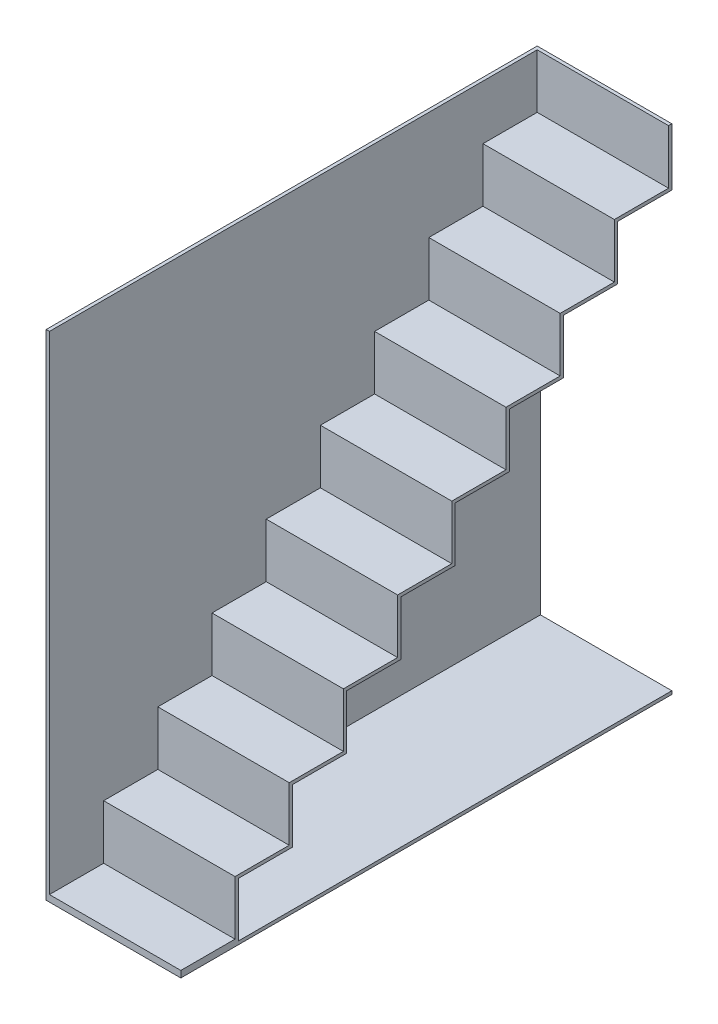
SolidWorks part; units mm, degrees
ref_plane "Front Plane" through (0, 0, 0) normal (0, 0, 1) x (1, 0, 0)
ref_plane "Top Plane" through (0, 0, 0) normal (0, 1, 0) x (1, 0, 0)
ref_plane "Right Plane" through (0, 0, 0) normal (1, 0, 0) x (0, 0, -1)
sketch "Sketch1" plane through (0, 0, 0) normal (1, 0, 0) x (0, 0, -1)
  line L0 (-23.9317, -26.5974) -> (-23.9317, 6.4026)
  line L1 (-25.9317, -24.5974) -> (-25.9317, 8.4026)
  line L3 (-25.9317, 8.4026) -> (7.0683, 8.4026)
  line L4 (-23.9317, 6.4026) -> (9.0683, 6.4026)
  line L6 (9.0683, 6.4026) -> (9.0683, 39.4026)
  line L7 (-23.9317, -26.5974) -> (-23.9317, 8.4026) construction
  line L8 (-25.9317, 6.4026) -> (9.0683, 6.4026) construction
  line L9 (7.0683, 8.4026) -> (7.0683, 41.4026)
  line L12 (-25.9317, 8.4026) -> (9.0683, 8.4026) construction
  line L13 (7.0683, 6.4026) -> (7.0683, 41.4026) construction
  line L14 (9.0683, 39.4026) -> (42.0683, 39.4026)
  line L16 (7.0683, 41.4026) -> (40.0683, 41.4026)
  line L17 (9.0683, 6.4026) -> (9.0683, 41.4026) construction
  line L18 (-23.9317, -26.5974) -> (-58.9317, -26.5974)
  line L19 (-25.9317, -24.5974) -> (-58.9317, -24.5974)
  line L20 (-58.9317, -24.5974) -> (-58.9317, -26.5974)
  line L22 (-25.9317, -26.5974) -> (-25.9317, 8.4026) construction
  line L23 (-23.9317, -24.5974) -> (-58.9317, -24.5974) construction
  line L24 (40.0683, 41.4026) -> (40.0683, 74.4026)
  line L26 (42.0683, 39.4026) -> (42.0683, 72.4026)
  line L27 (40.0683, 74.4026) -> (73.0683, 74.4026)
  line L28 (42.0683, 72.4026) -> (75.0683, 72.4026)
  line L30 (40.0683, 72.4026) -> (75.0683, 72.4026) construction
  line L31 (75.0683, 72.4026) -> (75.0683, 105.4026)
  line L32 (73.0683, 74.4026) -> (73.0683, 107.4026)
  line L34 (73.0683, 107.4026) -> (106.0683, 107.4026)
  line L35 (40.0683, 74.4026) -> (75.0683, 74.4026) construction
  line L36 (73.0683, 72.4026) -> (73.0683, 107.4026) construction
  line L37 (75.0683, 105.4026) -> (108.0683, 105.4026)
  line L39 (108.0683, 105.4026) -> (108.0683, 138.4026)
  line L40 (73.0683, 105.4026) -> (108.0683, 105.4026) construction
  line L41 (75.0683, 72.4026) -> (75.0683, 107.4026) construction
  line L42 (106.0683, 107.4026) -> (106.0683, 140.4026)
  line L44 (106.0683, 140.4026) -> (139.0683, 140.4026)
  line L45 (73.0683, 107.4026) -> (108.0683, 107.4026) construction
  line L46 (106.0683, 105.4026) -> (106.0683, 140.4026) construction
  line L47 (108.0683, 138.4026) -> (141.0683, 138.4026)
  line L49 (141.0683, 138.4026) -> (141.0683, 171.4026)
  line L50 (108.0683, 105.4026) -> (108.0683, 140.4026) construction
  line L51 (106.0683, 138.4026) -> (141.0683, 138.4026) construction
  line L52 (139.0683, 140.4026) -> (139.0683, 173.4026)
  line L54 (139.0683, 173.4026) -> (172.0683, 173.4026)
  line L55 (106.0683, 140.4026) -> (141.0683, 140.4026) construction
  line L56 (139.0683, 138.4026) -> (139.0683, 173.4026) construction
  line L57 (141.0683, 171.4026) -> (174.0683, 171.4026)
  line L59 (174.0683, 171.4026) -> (174.0683, 204.4026)
  line L60 (141.0683, 138.4026) -> (141.0683, 173.4026) construction
  line L61 (139.0683, 171.4026) -> (174.0683, 171.4026) construction
  line L62 (172.0683, 173.4026) -> (172.0683, 206.4026)
  line L64 (172.0683, 206.4026) -> (205.0683, 206.4026)
  line L65 (139.0683, 173.4026) -> (174.0683, 173.4026) construction
  line L66 (172.0683, 171.4026) -> (172.0683, 206.4026) construction
  line L67 (174.0683, 204.4026) -> (207.0683, 204.4026)
  line L69 (207.0683, 204.4026) -> (207.0683, 237.4026)
  line L70 (174.0683, 171.4026) -> (174.0683, 206.4026) construction
  line L71 (172.0683, 204.4026) -> (207.0683, 204.4026) construction
  line L72 (205.0683, 206.4026) -> (205.0683, 239.4026)
  line L74 (205.0683, 239.4026) -> (238.0683, 239.4026)
  line L75 (172.0683, 206.4026) -> (207.0683, 206.4026) construction
  line L76 (205.0683, 204.4026) -> (205.0683, 239.4026) construction
  line L77 (207.0683, 237.4026) -> (240.0683, 237.4026)
  line L79 (240.0683, 237.4026) -> (240.0683, 272.4026)
  line L80 (207.0683, 204.4026) -> (207.0683, 239.4026) construction
  line L81 (205.0683, 237.4026) -> (240.0683, 237.4026) construction
  line L82 (238.0683, 239.4026) -> (238.0683, 272.4026)
  line L83 (238.0683, 272.4026) -> (240.0683, 272.4026)
  line L85 (205.0683, 239.4026) -> (240.0683, 239.4026) construction
  line L86 (238.0683, 237.4026) -> (238.0683, 272.4026) construction
  point P12 (7.0683, 39.4026)
  point P13 (42.0683, 41.4026)
  point P20 (40.0683, 39.4026)
  dimension "D3" = 35
  dimension "D5" = 2
  dimension "D7" = 35
  dimension "D8" = 2
  dimension "D9" = 299
  dimension "D10" = 35
  dimension "D21" = 35
  dimension "D1" = 2
  dimension "D4" = 2
  dimension "D6" = 2
  dimension "D11" = 2
  dimension "D12" = 2
  dimension "D13" = 2
  dimension "D14" = 2
  dimension "D15" = 2
  dimension "D16" = 2
  dimension "D17" = 2
  dimension "D18" = 2
  dimension "D19" = 2
  dimension "D20" = 2
  dimension "D22" = 2
extrude "Boss-Extrude1" add sketch "Sketch1" along normal blind 80
sketch "Sketch3" plane through (0, 0, 0) normal (-1, 0, 0) x (0, 0, 1)
  line L1 (-240.0683, 272.4026) -> (58.9317, 272.4026)
  line L2 (-240.0683, 272.4026) -> (-240.0683, -26.5974)
  line L3 (-240.0683, -26.5974) -> (58.9317, -26.5974)
  line L4 (58.9317, 272.4026) -> (58.9317, -26.5974)
extrude "Boss-Extrude2" add sketch "Sketch3" along normal blind 2
sketch "Sketch4" plane through (0, -26.5974, 0) normal (0, -1, 0) x (1, 0, 0)
  line L0 (80, -207.0683) -> (80, -240.0683) construction
  line L1 (-2, 58.9317) -> (80, 58.9317)
  line L2 (-2, 58.9317) -> (-2, -240.0683)
  line L3 (-2, -240.0683) -> (80, -240.0683)
  line L4 (80, 58.9317) -> (80, -240.0683)
extrude "Boss-Extrude3" add sketch "Sketch4" along normal blind 2
sketch "Sketch6" plane through (-2, 0, 0) normal (-1, 0, 0) x (0, 0, 1)
  line L0 (-240.0683, 121.9026) -> (58.9317, 121.9026) construction
  line L1 (-240.0683, 272.4026) -> (-240.0683, -28.5974) construction
  line L2 (58.9317, -28.5974) -> (58.9317, 272.4026) construction
